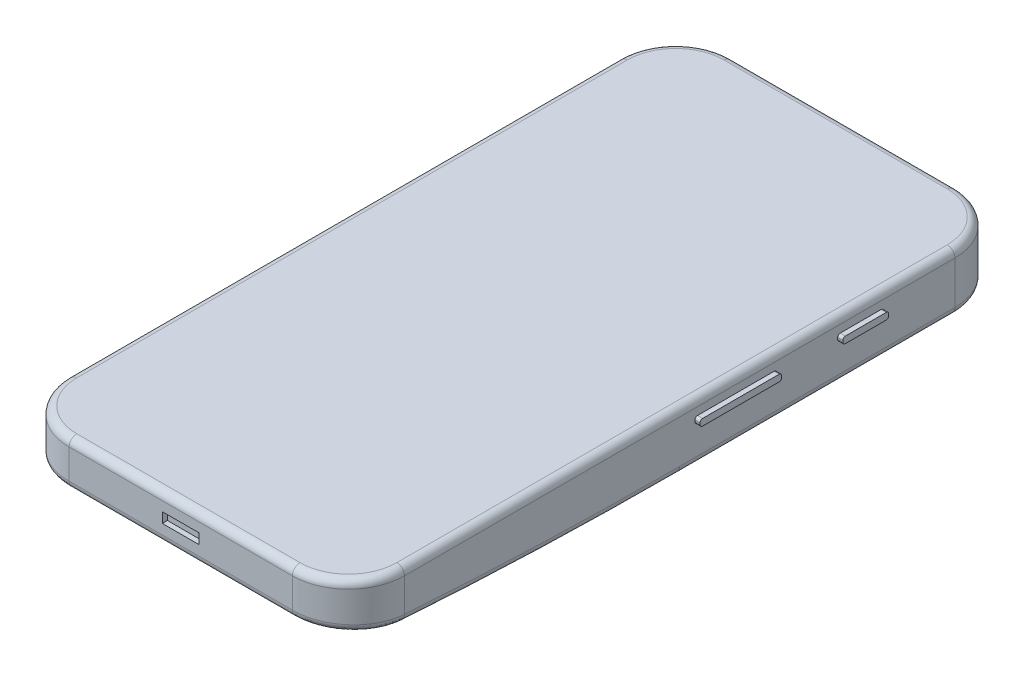
SolidWorks part; units mm, degrees
ref_plane "Front" through (0, 0, 0) normal (0, 0, 1) x (1, 0, 0)
ref_plane "Top" through (0, 0, 0) normal (0, 1, 0) x (1, 0, 0)
ref_plane "Right" through (0, 0, 0) normal (1, 0, 0) x (0, 0, -1)
sketch "Sketch1" plane through (0, 0, 0) normal (0, 1, 0) x (1, 0, 0)
  line L1 (-32.9, 65) -> (32.9, 65)
  line L2 (-32.9, 65) -> (-32.9, -65)
  line L3 (-32.9, -65) -> (32.9, -65)
  line L4 (32.9, 65) -> (32.9, -65)
  line L5 (-32.9, 65) -> (32.9, -65) construction
  line L6 (-32.9, -65) -> (32.9, 65) construction
  point P0 (0, 0)
  dimension "D1" = 65.8
  dimension "D2" = 130
extrude "Boss-Extrude1" add sketch "Sketch1" along normal blind 11.4
sketch "Sketch2" plane through (32.9, 0, 0) normal (1, 0, 0) x (0, 0, -1)
  line L0 (-65, 11.4) -> (-65, 0) construction
  line L1 (-65, 11.4) -> (65, 11.4) construction
  line L2 (-65, 2.7) -> (-65, 0)
  line L3 (-65, 0) -> (0, 0)
  arc A0 (0, 0) -> (-65, 2.7) centre (0, 783.7574) cw
  dimension "D1" = 8.7
extrude "Cut-Extrude1" cut sketch "Sketch2" against normal through all
fillet "Fillet1" radius 11 4 edges at (-32.9, 5.7, -65) (32.9, 5.7, -65) (32.9, 7.05, 65) (-32.9, 7.05, 65)
sketch "Sketch3" plane through (0, 0, 0) normal (0, -1, 0) x (1, 0, 0)
  line L0 (21.9, -65) -> (-21.9, -65) construction
  circle A0 centre (0, -44.1) radius 5.5
  circle A1 centre (0, -30.7) radius 2.75
  dimension "D3" = 11
  dimension "D4" = 5.5
  dimension "D1" = 20.9
  dimension "D2" = 34.3
extrude "Cut-Extrude2" cut sketch "Sketch3" against normal blind 1
sketch "Sketch4" plane through (32.9, 0, 0) normal (1, 0, 0) x (0, 0, -1)
  line L0 (-54, 11.4) -> (54, 11.4) construction
  line L1 (3, 8.4) -> (19, 8.4)
  line L2 (3, 8.4) -> (3, 7.1)
  line L3 (3, 7.1) -> (19, 7.1)
  line L4 (19, 8.4) -> (19, 7.1)
  line L5 (3, 8.4) -> (19, 7.1) construction
  line L6 (3, 7.1) -> (19, 8.4) construction
  line L7 (31, 8.4) -> (40, 8.4)
  line L8 (31, 8.4) -> (31, 7.1)
  line L9 (31, 7.1) -> (40, 7.1)
  line L10 (40, 8.4) -> (40, 7.1)
  line L11 (31, 8.4) -> (40, 7.1) construction
  line L12 (31, 7.1) -> (40, 8.4) construction
  line L13 (65, 11.4) -> (65, 0) construction
  point P0 (11, 7.75)
  point P5 (35.5, 7.75)
  dimension "D1" = 9
  dimension "D2" = 16
  dimension "D3" = 3
  dimension "D4" = 1.3
  dimension "D5" = 25
  dimension "D6" = 46
extrude "Boss-Extrude2" add sketch "Sketch4" along normal blind 1
sketch "Sketch5" plane through (0, 0, 65) normal (0, 0, 1) x (1, 0, 0)
  line L0 (0, 11.4) -> (0, 7.05) construction
  line L1 (-3.6, 8.05) -> (3.6, 8.05)
  line L2 (-3.6, 8.05) -> (-3.6, 6.05)
  line L3 (-3.6, 6.05) -> (3.6, 6.05)
  line L4 (3.6, 8.05) -> (3.6, 6.05)
  line L5 (-3.6, 8.05) -> (3.6, 6.05) construction
  line L6 (-3.6, 6.05) -> (3.6, 8.05) construction
  line L7 (-21.9, 11.4) -> (21.9, 11.4) construction
  line L8 (0, 7.05) -> (0, 2.7) construction
  line L9 (-21.9, 2.7) -> (21.9, 2.7) construction
  point P0 (0, 7.05)
  dimension "D1" = 7.2
  dimension "D2" = 2
extrude "Cut-Extrude3" cut sketch "Sketch5" against normal blind 1
fillet "Fillet2" radius 0.5 8 edges at (33.4, 7.1, -40) (33.4, 7.1, -19) (33.4, 8.4, -40) (33.4, 7.1, -31) (33.4, 8.4, -31) (33.4, 8.4, -19) (33.4, 7.1, -3) (33.4, 8.4, -3)
fillet "Fillet3" radius 1.5 18 edges at (-28.7546, 2.5042, 62.6032) (-32.9, 0.4658, 27.0161) (-32.9, 0, -27) (-29.6782, 0, -61.7782) (0, 0, -65) (29.6782, 0, -61.7782) (32.9, 0, -27) (32.9, 0.4658, 27.0161) (30.4784, 2.3685, 60.8856) (29.6782, 11.4, 61.7782) (0, 11.4, 65) (-29.6782, 11.4, 61.7782) (-32.9, 11.4, 0) (-29.6782, 11.4, -61.7782) (0, 11.4, -65) (29.6782, 11.4, -61.7782) (0, 2.7, 65) (32.9, 11.4, 0)
